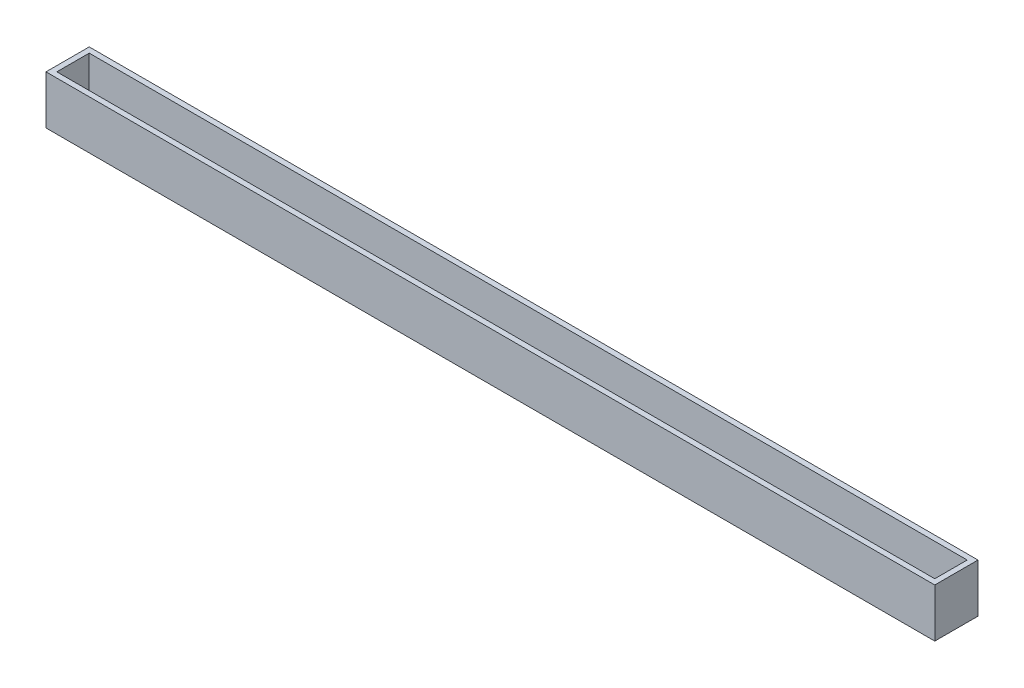
SolidWorks part; units mm, degrees
ref_plane "Спереди" through (0, 0, 0) normal (0, 0, 1) x (1, 0, 0)
ref_plane "Сверху" through (0, 0, 0) normal (0, 1, 0) x (1, 0, 0)
ref_plane "Справа" through (0, 0, 0) normal (1, 0, 0) x (0, 0, -1)
sketch "Эскиз1" plane through (0, 0, 0) normal (0, 1, 0) x (1, 0, 0)
  line L1 (-1645, -80) -> (1645, -80)
  line L2 (-1645, -80) -> (-1645, 80)
  line L3 (-1645, 80) -> (1645, 80)
  line L4 (1645, -80) -> (1645, 80)
  line L5 (-1645, -80) -> (1645, 80) construction
  line L6 (-1645, 80) -> (1645, -80) construction
  point P0 (0, 0)
  point P6 (1645, 0)
  dimension "D1" = 3290
  dimension "D2" = 160
extrude "Бобышка-Вытянуть1" add sketch "Эскиз1" along normal blind 180
shell "Оболочка1" thickness 20
